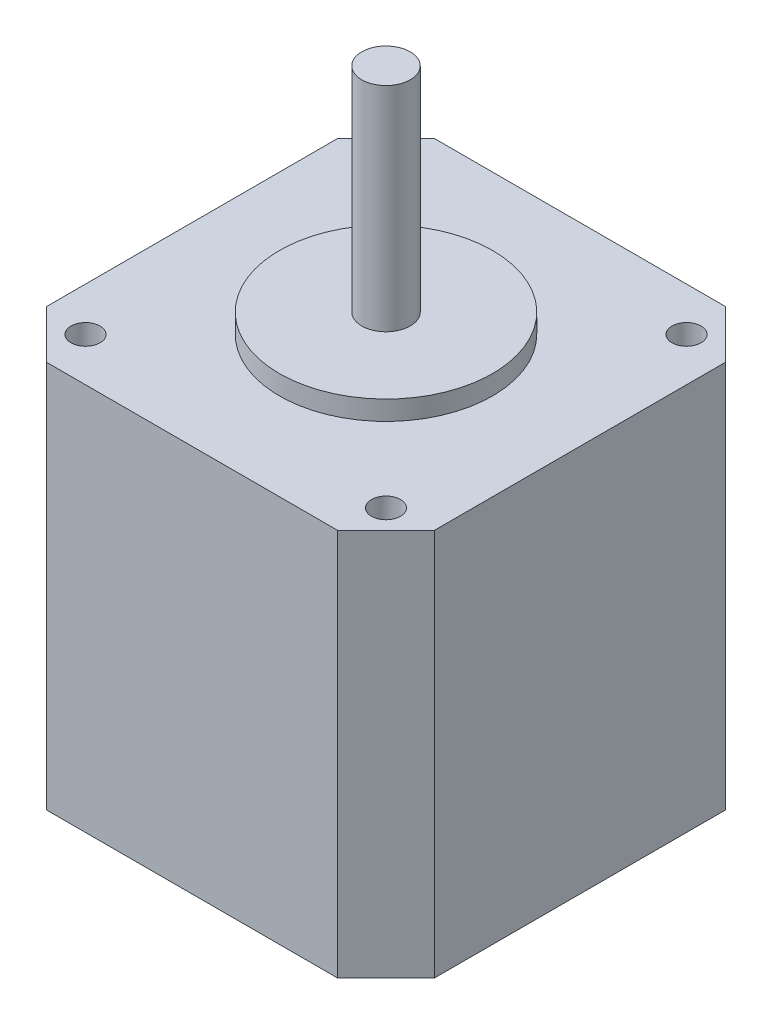
SolidWorks part; units mm, degrees
ref_plane "Front Plane" through (0, 0, 0) normal (0, 0, 1) x (1, 0, 0)
ref_plane "Top Plane" through (0, 0, 0) normal (0, 1, 0) x (1, 0, 0)
ref_plane "Right Plane" through (0, 0, 0) normal (1, 0, 0) x (0, 0, -1)
sketch "Sketch1" plane through (0, 0, 0) normal (0, 1, 0) x (1, 0, 0)
  line L0 (0, 35) -> (5, 40)
  line L1 (5, 0) -> (35, 0)
  line L2 (0, 5) -> (0, 35)
  line L3 (5, 40) -> (35, 40)
  line L4 (40, 5) -> (40, 35)
  line L5 (35, 40) -> (40, 35)
  line L6 (35, 0) -> (40, 5)
  line L7 (0, 5) -> (5, 0)
  point P0 (0, 0)
  point P1 (40, 40)
  point P2 (0, 40)
  point P3 (40, 0)
  dimension "D1" = 40
  dimension "D2" = 40
extrude "Boss-Extrude1" add sketch "Sketch1" along normal blind 40
sketch "Sketch2" plane through (0, 40, 0) normal (0, 1, 0) x (1, 0, 0)
  line L0 (0, 35) -> (0, 5) construction
  line L2 (0, 20) -> (40, 20) construction
  line L3 (40, 5) -> (40, 35) construction
  circle A0 centre (20, 20) radius 11
  point P12 (20, 20)
  dimension "D1" = 22
extrude "Boss-Extrude2" add sketch "Sketch2" along normal blind 2
sketch "Sketch3" plane through (0, 42, 0) normal (0, 1, 0) x (1, 0, 0)
  circle A0 centre (20, 20) radius 2.5
  dimension "D1" = 5
extrude "Boss-Extrude3" add sketch "Sketch3" along normal blind 22
sketch "Sketch4" plane through (0, 0, 0) normal (0, -1, 0) x (1, 0, 0)
  line L0 (20, 0) -> (20, -40) construction
  line L1 (5, 0) -> (35, 0) construction
  line L2 (35, -40) -> (5, -40) construction
  line L3 (0, -20) -> (40, -20) construction
  line L4 (0, -35) -> (0, -5) construction
  line L5 (40, -5) -> (40, -35) construction
  circle A0 centre (4.5, -4.5) radius 1.5
  dimension "D1" = 3
  dimension "D3" = 15.5
  dimension "D2" = 15.5
extrude "Cut-Extrude1" cut sketch "Sketch4" against normal through all
pattern_linear "LPattern1" count 2 spacing 31 along (1, 0, 0) count 2 spacing 31 along (0, 0, -1) of "Cut-Extrude1"
